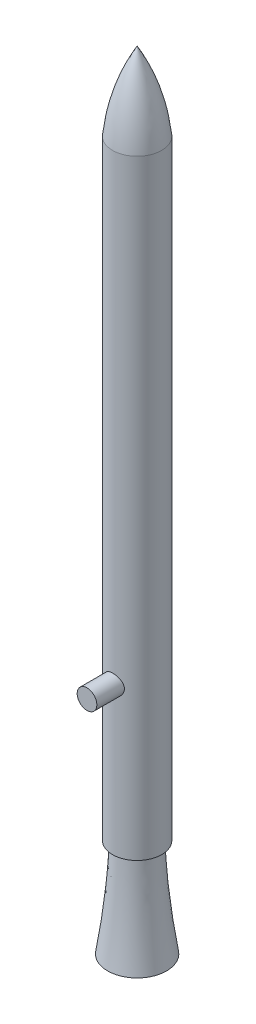
SolidWorks part; units mm, degrees
ref_plane "Front Plane" through (0, 0, 0) normal (0, 0, 1) x (1, 0, 0)
ref_plane "Top Plane" through (0, 0, 0) normal (0, 1, 0) x (1, 0, 0)
ref_plane "Right Plane" through (0, 0, 0) normal (1, 0, 0) x (0, 0, -1)
sketch "Sketch1" plane through (0, 0, 0) normal (0, 0, 1) x (1, 0, 0)
  line L0 (0, 8000) -> (0, 1000)
  line L1 (250, 7205.0451) -> (250, 1000)
  line L2 (250, 1000) -> (200, 1000)
  line L3 (300, 0) -> (150, 0)
  line L4 (50, 1000) -> (0, 1000)
  line L5 (0, 402.4954) -> (0, -229.8529) construction
  spline S0 degree 2 poles (200, 1000) (219.1096, 496.9115) (300, 0) knots 0 0 0 1 1 1
  spline S1 degree 2 poles (50, 1000) (88.9264, 498.8925) (150, 0) knots 0 0 0 1 1 1
  spline S2 degree 2 poles (0, 8000) (210.009, 7628.4495) (250, 7205.0451) knots 0 0 0 1 1 1
  dimension "D1" = 50
  dimension "D2" = 250
  dimension "D3" = 50
  dimension "D4" = 150
  dimension "D9" = 150
revolve "Revolve1" add sketch "Sketch1" angle 360 about L5
sketch "Sketch2" plane through (0, 0, 0) normal (0, 0, 1) x (1, 0, 0)
  line L0 (-200, 1000) -> (200, 1000) construction
  circle A0 centre (0, 2500) radius 100
  dimension "D1" = 1500
extrude "Boss-Extrude1" add sketch "Sketch2" along normal blind 510
sketch "Sketch3" plane through (0, 0, 0) normal (0, 0, 1) x (1, 0, 0)
  circle A0 centre (0, 2500) radius 50
  dimension "D1" = 100
extrude "Cut-Extrude1" cut sketch "Sketch3" against normal blind 510
